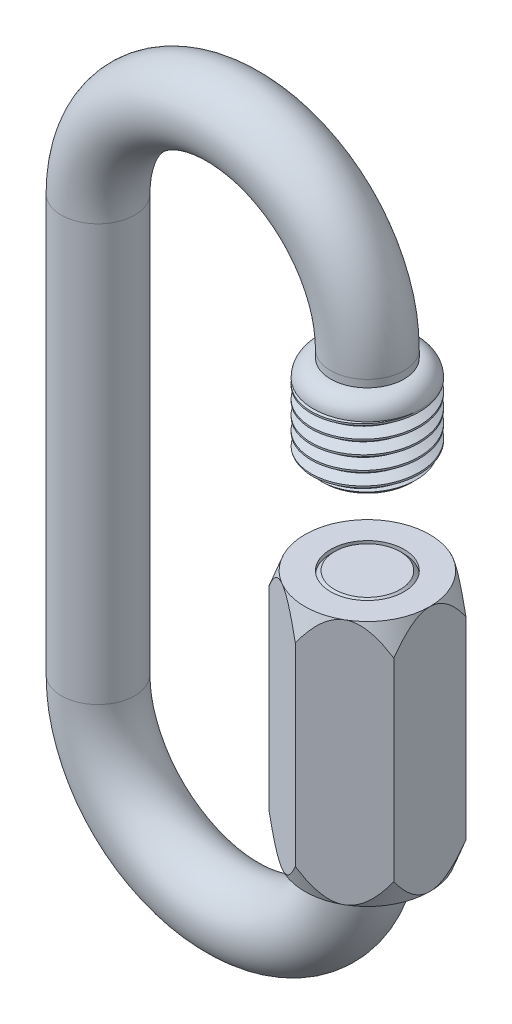
SolidWorks part; units mm, degrees
ref_plane "Front Plane" through (0, 0, 0) normal (0, 0, 1) x (1, 0, 0)
ref_plane "Top Plane" through (0, 0, 0) normal (0, 1, 0) x (1, 0, 0)
ref_plane "Right Plane" through (0, 0, 0) normal (1, 0, 0) x (0, 0, -1)
sketch "Sketch1" plane through (0, 0, 0) normal (0, 0, 1) x (1, 0, 0)
  line L0 (6.35, 13.4938) -> (6.35, 13.0175) construction
  line L1 (-11.1125, 24.6063) -> (11.1125, 24.6063) construction
  line L2 (-11.1125, 24.6063) -> (-11.1125, -24.6063) construction
  line L3 (-11.1125, -24.6063) -> (11.1125, -24.6063) construction
  line L4 (11.1125, 24.6063) -> (11.1125, 13.4938) construction
  line L5 (4.6831, 1.0775) -> (12.7794, 1.0775) construction
  line L6 (4.6831, 1.0775) -> (4.6831, -14.9225) construction
  line L7 (4.6831, -14.9225) -> (12.7794, -14.9225) construction
  line L8 (12.7794, 1.0775) -> (12.7794, -14.9225) construction
  line L9 (-11.1125, 0) -> (-6.35, 0) construction
  line L10 (-6.35, -13.4938) -> (-6.35, 13.4938) construction
  line L11 (6.35, 1.0775) -> (6.35, -13.4938) construction
  line L12 (6.35, -13.4938) -> (11.1125, -13.4938) construction
  line L13 (11.1125, 1.0775) -> (11.1125, -24.6063) construction
  line L14 (11.1125, 13.4938) -> (11.1125, 13.0175) construction
  line L15 (12.2313, 13.0175) -> (5.2313, 13.0175) construction
  line L16 (5.2313, 13.0175) -> (5.2313, 7.4275) construction
  line L17 (5.2313, 7.4275) -> (12.2313, 7.4275) construction
  line L18 (12.2313, 7.4275) -> (12.2313, 13.0175) construction
  line L19 (12.326, 7.4822) -> (12.326, 6.6072) construction
  line L20 (12.326, 6.6072) -> (11.5682, 7.0447) construction
  line L21 (11.5682, 7.0447) -> (12.326, 7.4822) construction
  line L22 (11.5682, 7.0447) -> (11.6629, 7.0447) construction
  line L23 (11.6629, 7.0994) -> (11.6629, 6.99) construction
  line L24 (12.326, 7.0447) -> (12.2313, 7.0447) construction
  line L25 (12.2313, 6.6619) -> (12.2313, 7.4275) construction
  line L26 (12.2786, 7.0447) -> (12.2786, 7.4548) construction
  line L27 (12.2786, 7.0447) -> (12.2786, 6.6345) construction
  line L28 (11.575, 7.4275) -> (12.2313, 8.0838) construction
  arc A0 (-11.1125, 13.4938) -> (11.1125, 13.4938) centre (0, 13.4938) cw construction
  arc A1 (-11.1125, -13.4938) -> (11.1125, -13.4938) centre (0, -13.4938) ccw construction
  arc A2 (6.35, 13.4938) -> (-6.35, 13.4938) centre (0, 13.4938) ccw construction
  arc A3 (-6.35, -13.4938) -> (6.35, -13.4938) centre (0, -13.4938) ccw construction
  arc A4 (11.1125, 13.0175) -> (12.2313, 11.8988) centre (11.1125, 11.8988) cw construction
  point P4 (-11.1125, 0)
  point P5 (0, 24.6063)
  point P21 (8.7313, -13.4938)
  point P22 (8.7313, -14.9225)
  point P28 (-6.35, -24.6063)
  point P29 (6.35, -24.6063)
  point P35 (8.7313, 7.4275)
  point P36 (8.7313, 1.0775)
  point P49 (-8.7312, 0)
  point P54 (0, -19.8438)
  point P55 (0, 19.8438)
  point P56 (-11.1125, 19.8438)
  point P57 (-11.1125, -19.8438)
  dimension "Hex Flats" = 8.0962
  dimension "Thickness" = 4.7625
  dimension "Inside Length" = 39.6875
  dimension "Inside Width" = 12.7
  dimension "Hex Length" = 16
  dimension "Opening Width" = 6.35
  dimension "Thread Diameter" = 7
  dimension "D3" = 0.4763
  dimension "Pitch" = 0.875
  dimension "D4" = 0.1094
  dimension "D5" = 45
  dimension "D6" = 0.6563
  dimension "D1" = 5.59
ref_plane "Plane1" through (0, 13.0175, 0) normal (0, 1, 0) x (1, 0, 0)
sketch "Sketch2" plane through (0, 0, 0) normal (0, 1, 0) x (1, 0, 0)
  circle A0 centre (-8.7312, 0) radius 2.3813
sketch "Sketch3" plane through (0, 0, 0) normal (0, 0, 1) x (1, 0, 0)
  line L0 (4.6831, 1.0775) -> (12.7794, 1.0775) construction
  line L1 (12.2313, 13.0175) -> (5.2313, 13.0175) construction
  line L2 (8.7313, 13.0175) -> (8.7313, 7.4275)
  line L3 (5.2313, 7.4275) -> (12.2313, 7.4275) construction
  line L21 (8.7313, 1.0775) -> (8.7312, -13.4938)
  line L22 (-8.7312, -13.4938) -> (-8.7312, 13.4938)
  line L23 (8.7312, 13.4938) -> (8.7313, 13.0175)
  arc A0 (-6.35, -13.4938) -> (6.35, -13.4938) centre (0, -13.4938) ccw construction
  arc A1 (6.35, 13.4938) -> (-6.35, 13.4938) centre (0, 13.4938) ccw construction
  arc A16 (-8.7312, -13.4938) -> (8.7312, -13.4938) centre (0, -13.4938) ccw
  arc A17 (8.7312, 13.4938) -> (-8.7312, 13.4938) centre (0, 13.4938) ccw
sweep "Sweep1" add profiles "Sketch2" path "Sketch3"
sketch "Sketch5" plane through (0, 0, 0) normal (0, 0, 1) x (1, 0, 0)
  line L0 (5.2313, 7.4275) -> (12.2313, 7.4275) construction
  line L1 (11.575, 7.4275) -> (12.2313, 8.0838) construction
  line L2 (12.2313, 7.4275) -> (12.2313, 13.0175) construction
  line L3 (12.2313, 13.0175) -> (5.2313, 13.0175) construction
  line L4 (8.7313, 7.4275) -> (11.575, 7.4275)
  line L5 (11.575, 7.4275) -> (12.2313, 8.0838)
  line L6 (12.2313, 8.0838) -> (12.2313, 11.8988)
  line L7 (11.1125, 13.0175) -> (8.7313, 13.0175)
  line L8 (8.7313, 7.4275) -> (8.7313, 13.0175)
  arc A0 (12.2313, 11.8988) -> (11.1125, 13.0175) centre (11.1125, 11.8988) ccw construction
  arc A1 (12.2313, 11.8988) -> (11.1125, 13.0175) centre (11.1125, 11.8988) ccw
revolve "Revolve1" add sketch "Sketch5" angle 360 about L8
chamfer "Chamfer1" distance 0.254 angle 45 1 edges at (8.7313, 1.0775, 2.3813)
sketch "Sketch6" plane through (0, 0, 0) normal (0, 1, 0) x (1, 0, 0)
  line L0 (6.35, 0) -> (11.1125, 0) construction
  line L1 (12.7794, -2.3372) -> (12.7794, 2.3372)
  line L2 (12.7794, 2.3372) -> (8.7312, 4.6744)
  line L3 (8.7312, 4.6744) -> (4.6831, 2.3372)
  line L4 (4.6831, 2.3372) -> (4.6831, -2.3372)
  line L5 (4.6831, -2.3372) -> (8.7313, -4.6744)
  line L6 (8.7313, -4.6744) -> (12.7794, -2.3372)
  line L7 (6.35, 0) -> (11.1125, 0) construction
  circle A0 centre (8.7313, 0) radius 4.0481 construction
  circle A1 centre (8.7313, 0) radius 2.3813
extrude "Boss-Extrude1" add sketch "Sketch6" against normal up to vertex (14.9225 mm away) from vertex at 1.0775 separate body starting at point (4.6831, 1.0775, 0)
sketch "Sketch7" plane through (0, 1.0775, 0) normal (0, 1, 0) x (1, 0, 0)
  circle A0 centre (8.7313, 0) radius 4.0481 construction
  circle A1 centre (8.7313, 0) radius 4.0481
extrude "Cut-Extrude1" cut sketch "Sketch7" against normal through all draft 20 flip side to cut
sketch "Sketch8" plane through (0, -14.9225, 0) normal (0, -1, 0) x (1, 0, 0)
  circle A1 centre (8.7313, 0) radius 4.0481
  circle A2 centre (8.7313, 0) radius 4.0481
  dimension "D1" = 0
extrude "Cut-Extrude2" cut sketch "Sketch8" against normal through all draft 20 flip side to cut
sketch "Sketch9" plane through (0, 7.4275, 0) normal (0, -1, 0) x (1, 0, 0)
  circle A0 centre (8.7312, 0) radius 3.5
curve "Helix/Spiral1" pitch 0.875 height 6.465 turns 7.3886
split "Split1" trim tools "Plane1" bodies to split 105 resulting bodies 111 112 113
sketch "Sketch11" plane through (0, 0, 0) normal (0, 0, 1) x (1, 0, 0)
  line L0 (12.2786, 7.4548) -> (11.6629, 7.0994)
  line L1 (11.6629, 7.0994) -> (11.6629, 6.99)
  line L2 (11.6629, 6.99) -> (12.2786, 6.6345)
  line L3 (12.2786, 6.6345) -> (12.2786, 7.4548)
sweep "Cut-Sweep1" cut profiles "Sketch11" path "Helix/Spiral1"
sketch "Sketch12" plane through (0, 0, 0) normal (0, 0, 1) x (1, 0, 0)
  line L0 (11.1125, 13.4938) -> (11.1125, 13.0175)
  line L1 (11.1125, 13.4938) -> (8.7313, 13.4937)
  line L4 (8.7313, 13.0175) -> (8.7313, 7.4275) construction
  line L5 (5.2313, 7.4275) -> (12.2313, 7.4275) construction
  line L6 (12.2313, 13.0175) -> (5.2313, 13.0175) construction
  line L9 (6.35, 13.4937) -> (11.1125, 13.4937) construction
  line L10 (8.7313, 13.4937) -> (8.7313, 11.8988)
  line L11 (8.7313, 11.8988) -> (12.2313, 11.8988)
  arc A0 (12.2313, 11.8988) -> (11.1125, 13.0175) centre (11.1125, 11.8988) ccw construction
  arc A1 (12.2313, 11.8988) -> (11.1125, 13.0175) centre (11.1125, 11.8988) ccw
revolve "Revolve2" add sketch "Sketch12" angle 360 about L4
equation "\"Hex Flats@Sketch1\" = \"Thickness@Sketch1\" * 1.7"
equation "\"D3@Sketch1\"=\"Thickness@Sketch1\"*.1"
equation "\"D4@Sketch1\"=\"Pitch@Sketch1\"/8"
equation "\"D6@Sketch1\"=\"Pitch@Sketch1\"*.75"
equation "\"D3@Helix/Spiral1\"=\"D1@Sketch1\"+\"Pitch@Sketch1\""
equation "\"D4@Helix/Spiral1\"=\"Pitch@Sketch1\""
equation "\"Pitch@Sketch1\"=\"Thread Diameter@Sketch1\"*.125"
equation "\"D1@Sketch1\"=\"Inside Length@Sketch1\"-\"Inside Width@Sketch1\"-\"Hex Length@Sketch1\"-\"Opening Width@Sketch1\"+(2*\"D3@Sketch1\")"
